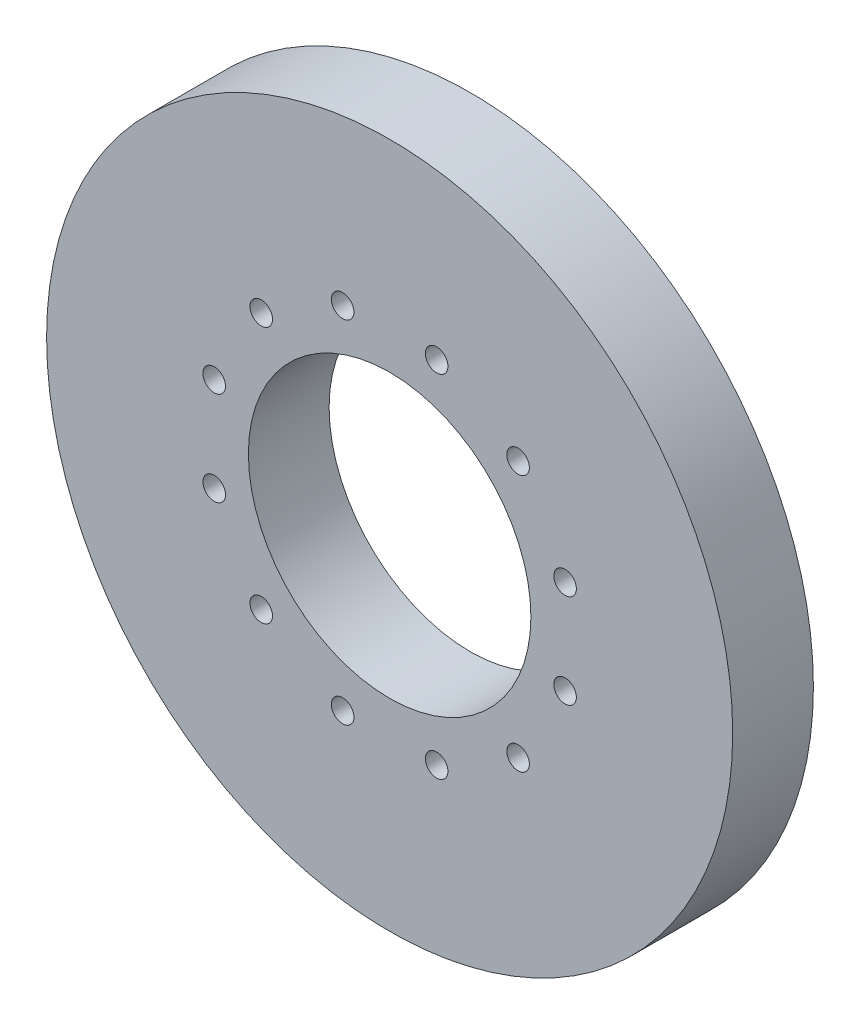
SolidWorks part; units mm, degrees
ref_plane "Front" through (0, 0, 0) normal (0, 0, 1) x (1, 0, 0)
ref_plane "Top" through (0, 0, 0) normal (0, 1, 0) x (1, 0, 0)
ref_plane "Right" through (0, 0, 0) normal (1, 0, 0) x (0, 0, -1)
sketch "Sketch1" plane through (0, 0, 0) normal (0, 0, 1) x (1, 0, 0)
  circle A0 centre (0, 0) radius 42.5
  circle A1 centre (0, 0) radius 17.5
  dimension "D1" = 85
  dimension "D2" = 35
extrude "Boss-Extrude1" add sketch "Sketch1" along normal blind 10
sketch "Sketch2" plane through (0, 0, 10) normal (0, 0, 1) x (1, 0, 0)
  line L0 (0, 0) -> (21.7333, 5.8234) construction
  circle A0 centre (21.7333, 5.8234) radius 1.4
  dimension "D1" = 2.8
  dimension "D2" = 22.5
  dimension "D3" = 15
extrude "Cut-Extrude1" cut sketch "Sketch2" against normal through all
pattern_circular "CirPattern1" count 12 over 360 about axis through (0, 0, 0) along (0, 0, 1) of "Cut-Extrude1"
